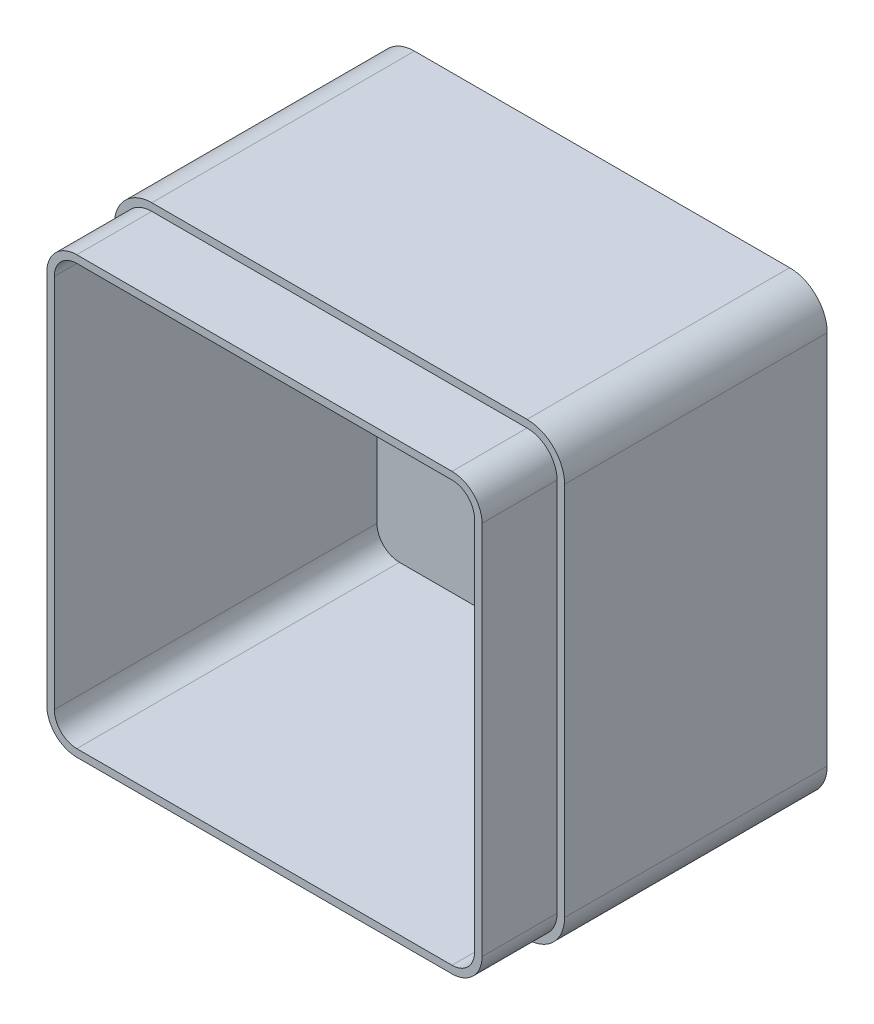
SolidWorks part; units mm, degrees
ref_plane "前视基准面" through (0, 0, 0) normal (0, 0, 1) x (1, 0, 0)
ref_plane "上视基准面" through (0, 0, 0) normal (0, 1, 0) x (1, 0, 0)
ref_plane "右视基准面" through (0, 0, 0) normal (1, 0, 0) x (0, 0, -1)
sketch "草图1" plane through (0, 0, 0) normal (0, 0, 1) x (1, 0, 0)
  line L1 (0, 0) -> (120, 0)
  line L2 (0, 0) -> (0, 120)
  line L3 (0, 120) -> (120, 120)
  line L4 (120, 0) -> (120, 120)
  dimension "D1" = 120
  dimension "D2" = 120
extrude "凸台-拉伸1" add sketch "草图1" along normal blind 90
fillet "圆角2" radius 10 4 edges at (0, 0, 45) (120, 0, 45) (0, 120, 45) (120, 120, 45)
shell "抽壳2" thickness 4
sketch "草图3" plane through (0, 0, 90) normal (0, 0, 1) x (1, 0, 0)
  line L0 (2, 110) -> (2, 10)
  line L1 (10, 2) -> (110, 2)
  line L2 (118, 10) -> (118, 110)
  line L3 (110, 118) -> (10, 118)
  line L4 (0, 110) -> (0, 10)
  line L5 (10, 0) -> (110, 0)
  line L6 (120, 10) -> (120, 110)
  line L7 (110, 120) -> (10, 120)
  line L8 (0, 110) -> (0, 10)
  line L9 (10, 0) -> (110, 0)
  line L10 (120, 10) -> (120, 110)
  line L11 (110, 120) -> (10, 120)
  arc A0 (2, 10) -> (10, 2) centre (10, 10) ccw
  arc A1 (110, 2) -> (118, 10) centre (110, 10) ccw
  arc A2 (118, 110) -> (110, 118) centre (110, 110) ccw
  arc A3 (10, 118) -> (2, 110) centre (10, 110) ccw
  arc A4 (0, 10) -> (10, 0) centre (10, 10) ccw
  arc A5 (110, 0) -> (120, 10) centre (110, 10) ccw
  arc A6 (120, 110) -> (110, 120) centre (110, 110) ccw
  arc A7 (10, 120) -> (0, 110) centre (10, 110) ccw
  arc A8 (0, 10) -> (10, 0) centre (10, 10) ccw
  arc A9 (110, 0) -> (120, 10) centre (110, 10) ccw
  arc A10 (120, 110) -> (110, 120) centre (110, 110) ccw
  arc A11 (10, 120) -> (0, 110) centre (10, 110) ccw
  dimension "D1" = 0
  dimension "D2" = 2
extrude "切除-拉伸2" cut sketch "草图3" against normal blind 20
